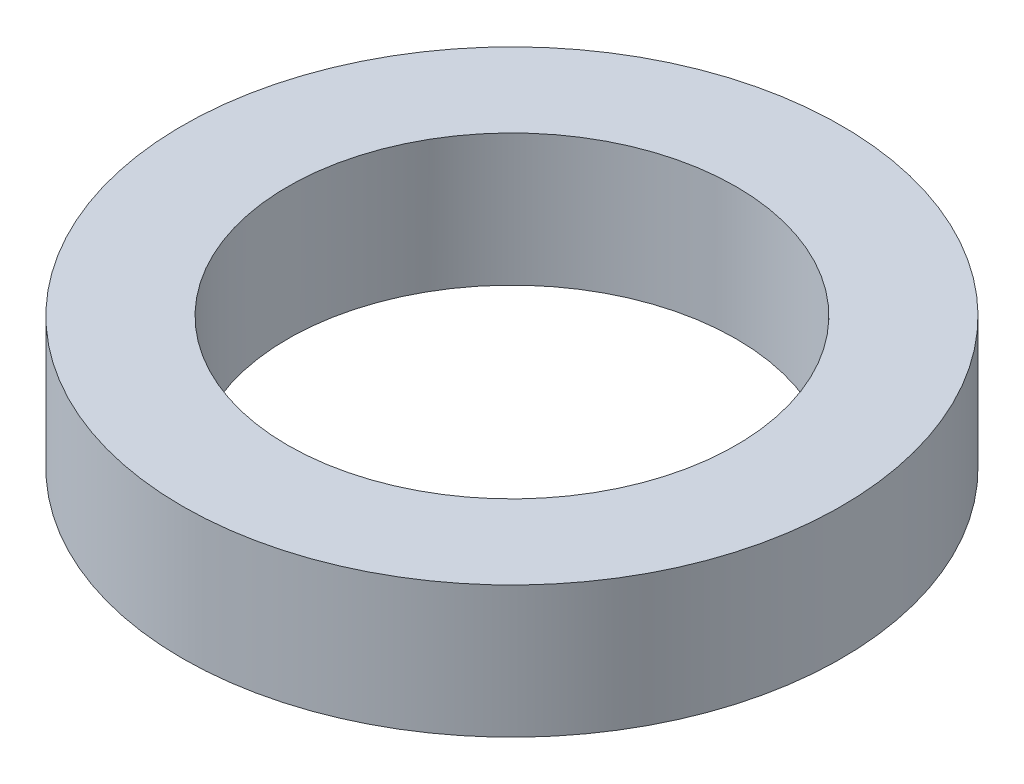
SolidWorks part; units mm, degrees
ref_plane "Front Plane" through (0, 0, 0) normal (0, 0, 1) x (1, 0, 0)
ref_plane "Top Plane" through (0, 0, 0) normal (0, 1, 0) x (1, 0, 0)
ref_plane "Right Plane" through (0, 0, 0) normal (1, 0, 0) x (0, 0, -1)
sketch "Sketch1" plane through (0, 0, 0) normal (0, 1, 0) x (1, 0, 0)
  circle A0 centre (0, 0) radius 2.5
  dimension "D1" = 5
extrude "Boss-Extrude1" add sketch "Sketch1" along normal blind 1
hole_wizard "M3 Clearance Hole1" positions "Sketch2" profile "Sketch3" hole size "M3" standard "ANSI Metric"
sketch "Sketch2" plane through (0, 0, 0) normal (0, -1, 0) x (-1, 0, 0)
  point P0 (0, 0)
sketch "Sketch3" plane through (0, 0, 0) normal (1, 0, 0) x (0, 0, -1)
  line L0 (0, 0) -> (0, 11.0215)
  line L1 (0, 11.0215) -> (1.7, 10)
  line L2 (1.7, 10) -> (1.7, 0)
  line L5 (1.7, 0) -> (0, 0)
  line L10 (0, 11.0215) -> (-1.7, 10) construction
  line L11 (0, -6.35) -> (0, 107.95) construction
  dimension "Hole Dia." = 3.4
  dimension "Hole Depth" = 10
  dimension "Drill Angle" = 118
